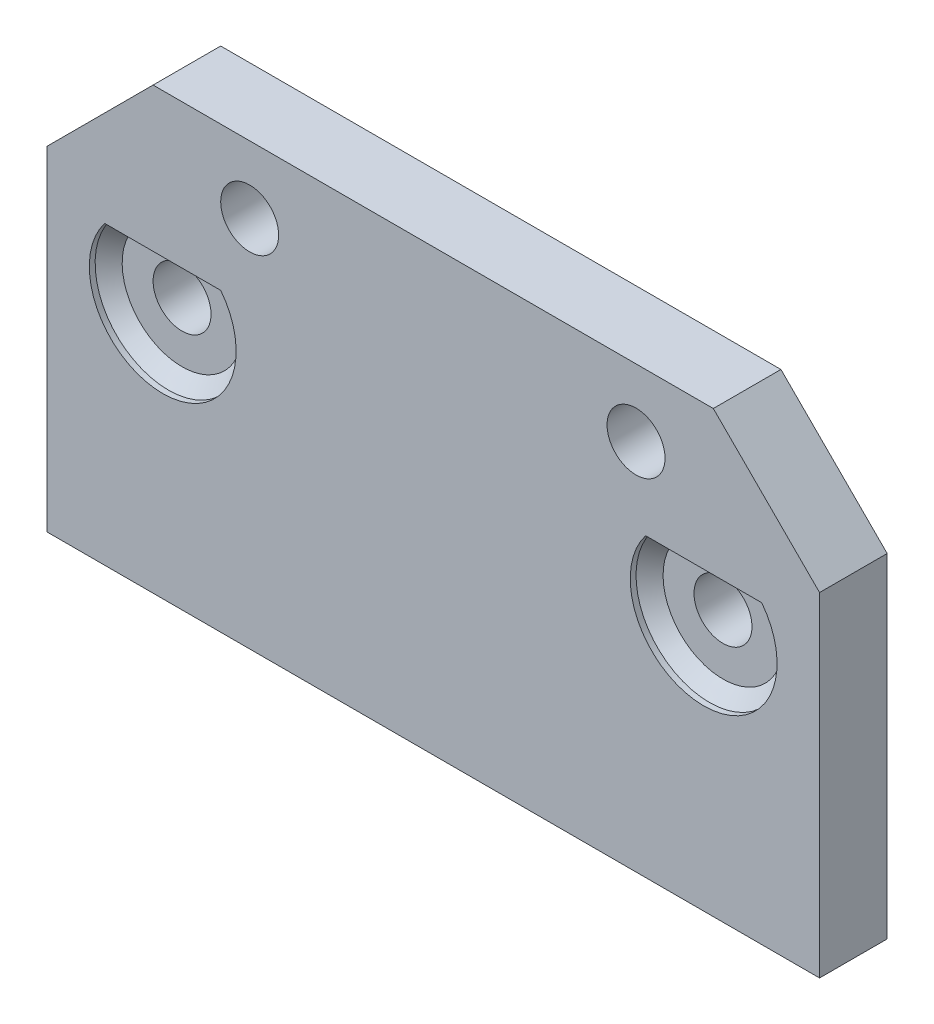
SolidWorks part; units mm, degrees
ref_plane "Спереди" through (0, 0, 0) normal (0, 0, 1) x (1, 0, 0)
ref_plane "Сверху" through (0, 0, 0) normal (0, 1, 0) x (1, 0, 0)
ref_plane "Справа" through (0, 0, 0) normal (1, 0, 0) x (0, 0, -1)
sketch "Эскиз1" plane through (0, 0, 0) normal (0, 1, 0) x (1, 0, 0)
  line L1 (-12.8378, 2.5) -> (27.1622, 2.5)
  line L2 (-12.8378, 2.5) -> (-12.8378, 0)
  line L3 (-12.8378, 0) -> (27.1622, 0)
  line L4 (27.1622, 2.5) -> (27.1622, 0)
  dimension "D1" = 2.5
  dimension "D2" = 40
extrude "Бобышка-Вытянуть1" add sketch "Эскиз1" along normal blind 18.5
sketch "Эскиз2" plane through (0, 0, 0) normal (0, 0, 1) x (1, 0, 0)
  line L0 (-12.8378, 3) -> (27.0188, 3) construction
  line L1 (-12.8378, 18.5) -> (-12.8378, 0) construction
  line L2 (-12.8378, 0) -> (27.1622, 0) construction
  line L3 (7.1622, 18.5) -> (7.1622, 0) construction
  line L4 (-12.8378, 18.5) -> (27.1622, 18.5) construction
  line L5 (-6.8378, 18.5) -> (-6.8378, 0) construction
  line L6 (21.1622, 18.5) -> (21.1622, 0) construction
  circle A0 centre (-6.8378, 3) radius 1.5
  circle A1 centre (21.1622, 3) radius 1.5
  dimension "D1" = 3
  dimension "D2" = 14
  dimension "D3" = 14
extrude "Вырез-Вытянуть1" cut sketch "Эскиз2" against normal through all
sketch "Эскиз3" plane through (0, 0, 0) normal (0, 0, 1) x (1, 0, 0)
  line L0 (-12.8378, 9.3) -> (27.0188, 9.3) construction
  line L1 (-12.8378, 18.5) -> (-12.8378, 0) construction
  line L2 (-2.3378, 18.5) -> (-2.3378, 0) construction
  line L3 (-12.8378, 18.5) -> (27.1622, 18.5) construction
  line L4 (-12.8378, 0) -> (27.1622, 0) construction
  line L5 (17.6622, 18.5) -> (17.6622, 0) construction
  line L6 (27.1622, 18.5) -> (27.1622, 0) construction
  circle A0 centre (-2.3378, 9.3) radius 1.5
  circle A1 centre (17.6622, 9.3) radius 1.5
  dimension "D2" = 9.2
  dimension "D1" = 20
  dimension "D3" = 9.5
extrude "Вырез-Вытянуть2" cut sketch "Эскиз3" against normal blind 40
sketch "Эскиз4" plane through (0, 0, 0) normal (0, 0, 1) x (1, 0, 0)
  line L0 (27.1622, 18.5) -> (27.1622, 0) construction
  line L1 (-12.8378, 18.5) -> (27.1622, 18.5)
  line L2 (-12.8378, 18.5) -> (-12.8378, 12.7801)
  line L3 (-12.8378, 12.7801) -> (27.1622, 12.7801)
  line L4 (27.1622, 18.5) -> (27.1622, 12.7801)
extrude "Вырез-Вытянуть3" cut sketch "Эскиз4" against normal blind 40
sketch "Эскиз5" plane through (0, 0, 0) normal (0, 0, 1) x (1, 0, 0)
  line L0 (-12.8378, 0) -> (27.1622, 0) construction
  line L1 (-12.8378, 12.7801) -> (27.1622, 12.7801)
  line L2 (-12.8378, 12.7801) -> (-12.8378, 0)
  line L3 (-12.8378, 0) -> (27.1622, 0)
  line L4 (27.1622, 12.7801) -> (27.1622, 0)
extrude "Бобышка-Вытянуть2" add sketch "Эскиз5" along normal blind 1
sketch "Эскиз6" plane through (0, 0, -2.5) normal (0, 0, -1) x (-1, 0, 0)
  circle A0 centre (-17.6622, 9.3) radius 1.5
  circle A1 centre (2.3378, 9.3) radius 1.5
  circle A2 centre (6.8378, 3) radius 1.5
  circle A3 centre (-21.1622, 3) radius 1.5
extrude "Вырез-Вытянуть4" cut sketch "Эскиз6" against normal through all
sketch "Эскиз8" plane through (0, 0, 0) normal (0, -1, 0) x (1, 0, 0)
  line L1 (-12.8378, 1) -> (27.1622, 1)
  line L2 (-12.8378, 1) -> (-12.8378, -2.5)
  line L3 (-12.8378, -2.5) -> (27.1622, -2.5)
  line L4 (27.1622, 1) -> (27.1622, -2.5)
extrude "Бобышка-Вытянуть3" add sketch "Эскиз8" along normal blind 5
sketch "Эскиз9" plane through (0, 0, 1) normal (0, 0, 1) x (1, 0, 0)
  circle A0 centre (-6.8378, 3) radius 3.8
  circle A1 centre (21.1622, 3) radius 3.8
extrude "Вырез-Вытянуть5" cut sketch "Эскиз9" against normal blind 1
sketch "Эскиз10" plane through (0, 0, -2.5) normal (0, 0, -1) x (-1, 0, 0)
  line L0 (-7.6622, 12.7801) -> (-7.6622, -5) construction
  line L1 (12.8378, 12.7801) -> (-27.1622, 12.7801) construction
  line L2 (12.8378, -5) -> (-27.1622, -5) construction
  line L3 (-17.6622, 10.8) -> (-17.6622, 7.8) construction
  line L4 (2.3378, 10.8) -> (2.3378, 7.8) construction
  line L6 (-13.6622, 12.7801) -> (-1.6622, 12.7801)
  line L7 (-13.6622, 12.7801) -> (-13.6622, -5)
  line L8 (-13.6622, -5) -> (-1.6622, -5)
  line L9 (-1.6622, 12.7801) -> (-1.6622, -5)
  circle A0 centre (-17.6622, 9.3) radius 1.5 construction
  circle A1 centre (2.3378, 9.3) radius 1.5 construction
  dimension "D1" = 10
  dimension "D2" = 12
  dimension "D3" = 6
extrude "Вырез-Вытянуть6" cut sketch "Эскиз10" against normal blind 1.5
chamfer "Фаска3" distance 0.7 angle 45 2 edges at (24.9622, 3, 0) (-3.0378, 3, 0)
sketch "Эскиз11" plane through (0, 0, 1) normal (0, 0, 1) x (1, 0, 0)
  line L0 (-12.8378, 12.7801) -> (-12.8378, 7.2801)
  line L1 (-12.8378, 12.7801) -> (-12.8378, -5) construction
  line L2 (-12.8378, 7.2801) -> (-7.3378, 12.7801)
  line L3 (27.1622, 12.7801) -> (-12.8378, 12.7801) construction
  line L4 (-7.3378, 12.7801) -> (-12.8378, 12.7801)
  line L5 (27.1622, 12.7801) -> (21.6622, 12.7801)
  line L6 (27.1622, -5) -> (27.1622, 12.7801) construction
  line L7 (21.6622, 12.7801) -> (27.1622, 7.2801)
  line L8 (27.1622, 7.2801) -> (27.1622, 12.7801)
  dimension "D1" = 5.5
  dimension "D2" = 5.5
  dimension "D3" = 5.5
  dimension "D4" = 5.5
extrude "Вырез-Вытянуть7" cut sketch "Эскиз11" against normal through all
sketch "Эскиз12" plane through (0, 0, 1) normal (0, 0, 1) x (1, 0, 0)
  line L0 (27.1622, -5) -> (27.1622, 7.2801) construction
  line L1 (-12.8378, 7.2801) -> (27.1622, 7.2801)
  line L2 (-12.8378, 7.2801) -> (-12.8378, 5.3262)
  line L3 (-12.8378, 5.3262) -> (27.1622, 5.3262)
  line L4 (27.1622, 7.2801) -> (27.1622, 5.3262)
  dimension "D1" = 1.9539
extrude "Бобышка-Вытянуть5" add sketch "Эскиз12" against normal blind 2
sketch "Эскиз13" plane through (0, -5, 0) normal (0, -1, 0) x (1, 0, 0)
  line L1 (-12.8378, 1) -> (27.1622, 1)
  line L2 (-12.8378, 1) -> (-12.8378, -2.5)
  line L3 (-12.8378, -2.5) -> (27.1622, -2.5)
  line L4 (27.1622, 1) -> (27.1622, -2.5)
extrude "Бобышка-Вытянуть6" add sketch "Эскиз13" along normal blind 5
sketch "Эскиз14" plane through (0, 0, -2.5) normal (0, 0, -1) x (-1, 0, 0)
  line L0 (-13.6622, 12.7801) -> (-13.6622, -5) construction
  line L1 (-13.6622, -0.6289) -> (-1.6622, -0.6289)
  line L2 (-13.6622, -0.6289) -> (-13.6622, -5)
  line L3 (-13.6622, -5) -> (-1.6622, -5)
  line L4 (-1.6622, -0.6289) -> (-1.6622, -5)
extrude "Бобышка-Вытянуть7" add sketch "Эскиз14" against normal blind 2
sketch "Эскиз15" plane through (0, 0, -2.5) normal (0, 0, -1) x (-1, 0, 0)
  line L0 (-1.6622, -0.6289) -> (-1.6622, 12.7801) construction
  line L1 (-13.6622, 12.7801) -> (-1.6622, 12.7801)
  line L2 (-13.6622, 12.7801) -> (-13.6622, 11.2351)
  line L3 (-13.6622, 11.2351) -> (-1.6622, 11.2351)
  line L4 (-1.6622, 12.7801) -> (-1.6622, 11.2351)
extrude "Бобышка-Вытянуть8" add sketch "Эскиз15" against normal blind 2
